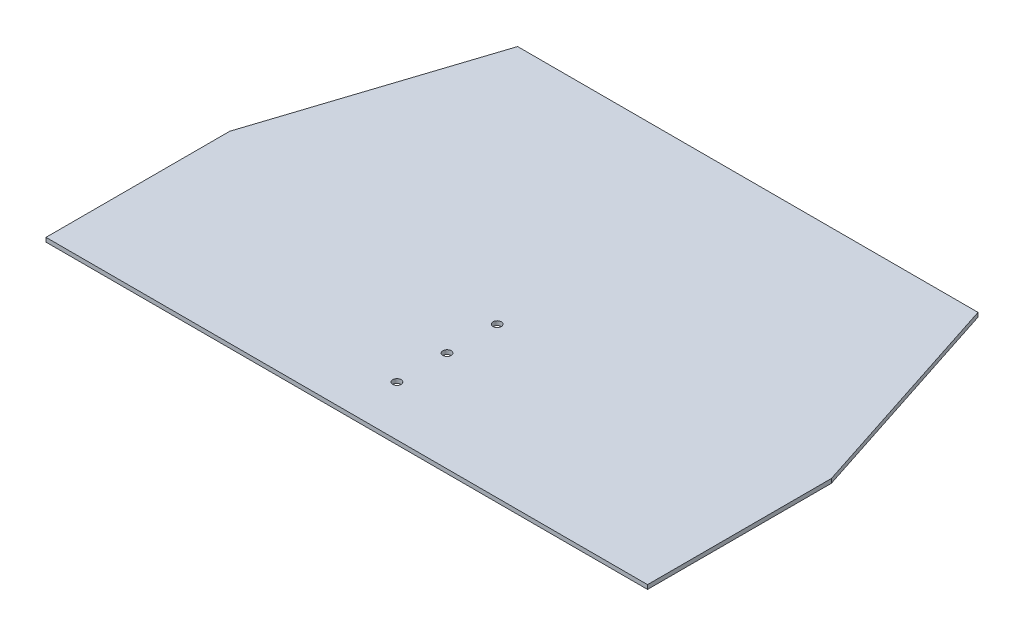
SolidWorks part; units mm, degrees
ref_plane "Front Plane" through (0, 0, 0) normal (0, 0, 1) x (1, 0, 0)
ref_plane "Top Plane" through (0, 0, 0) normal (0, 1, 0) x (1, 0, 0)
ref_plane "Right Plane" through (0, 0, 0) normal (1, 0, 0) x (0, 0, -1)
sketch "Sketch2" plane through (0, 0, 0) normal (0, 1, 0) x (1, 0, 0)
  line L1 (-228.6, -152.4) -> (228.6, -152.4)
  line L2 (-228.6, -152.4) -> (-228.6, 152.4)
  line L3 (-228.6, 152.4) -> (228.6, 152.4)
  line L4 (228.6, -152.4) -> (228.6, 152.4)
  line L5 (-228.6, -152.4) -> (228.6, 152.4) construction
  line L6 (-228.6, 152.4) -> (228.6, -152.4) construction
  point P0 (0, 0)
  dimension "D1" = 457.2
  dimension "D2" = 304.8
extrude "Boss-Extrude1" add sketch "Sketch2" along normal blind 3.175
sketch "Sketch3" plane through (0, 3.175, 0) normal (0, 1, 0) x (1, 0, 0)
  line L0 (-228.6, -12.7) -> (-174.9558, 152.4)
  line L1 (-228.6, 152.4) -> (-228.6, -152.4) construction
  line L2 (228.6, 152.4) -> (-228.6, 152.4) construction
  line L3 (-174.9558, 152.4) -> (-228.6, 152.4)
  line L4 (-228.6, 152.4) -> (-228.6, -12.7)
  line L5 (174.9558, 152.4) -> (228.6, 152.4)
  line L6 (228.6, 152.4) -> (228.6, -12.7)
  line L7 (228.6, -152.4) -> (228.6, 152.4) construction
  line L8 (228.6, -12.7) -> (174.9558, 152.4)
  line L9 (-228.6, -12.7) -> (228.6, -12.7) construction
  dimension "D1" = 18
  dimension "D2" = 165.1
extrude "Cut-Extrude1" cut sketch "Sketch3" against normal blind 3.175
sketch "Sketch5" plane through (0, 3.175, 0) normal (0, 1, 0) x (1, 0, 0)
  line L0 (0, 152.4) -> (0, -152.4) construction
  line L1 (174.9558, 152.4) -> (-174.9558, 152.4) construction
  line L2 (-228.6, -152.4) -> (228.6, -152.4) construction
  circle A0 centre (0, -114.3) radius 3.175
  circle A1 centre (0, -76.2) radius 3.175
  circle A2 centre (0, -38.1) radius 3.175
  dimension "D4" = 6.35
  dimension "D1" = 38.1
  dimension "D2" = 38.1
  dimension "D3" = 38.1
extrude "Cut-Extrude3" cut sketch "Sketch5" against normal blind 3.175
sketch "Sketch8" plane through (0, 3.175, 0) normal (0, 1, 0) x (1, 0, 0)
  line L0 (72.1065, 152.4) -> (140.357, -152.4) construction
  line L1 (37.2949, 307.8648) -> (185.8573, -355.6) construction
  line L2 (-228.6, -152.4) -> (228.6, -152.4) construction
  line L3 (174.9558, 152.4) -> (-174.9558, 152.4) construction
  line L4 (-72.3085, 152.4) -> (-140.559, -152.4) construction
  line L5 (-37.497, 307.8648) -> (-186.0594, -355.6) construction
sketch "Sketch9" plane through (0, 0, 0) normal (0, -1, 0) x (1, 0, 0)
  line L0 (46.0775, -152.4) -> (114.328, 152.4) construction
  line L1 (174.9558, -152.4) -> (-174.9558, -152.4) construction
  line L2 (-228.6, 152.4) -> (228.6, 152.4) construction
  line L3 (-46.2796, -152.4) -> (-114.5301, 152.4) construction
  line L4 (-72.3085, -152.4) -> (-140.559, 152.4) construction
  line L5 (72.1065, -152.4) -> (140.357, 152.4) construction
  dimension "D1" = 25.4
  dimension "D2" = 25.4
